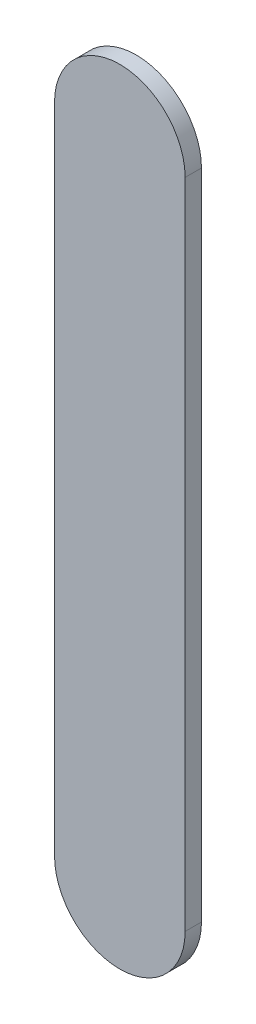
SolidWorks part; units mm, degrees
ref_plane "Front Plane" through (0, 0, 0) normal (0, 0, 1) x (1, 0, 0)
ref_plane "Top Plane" through (0, 0, 0) normal (0, 1, 0) x (1, 0, 0)
ref_plane "Right Plane" through (0, 0, 0) normal (1, 0, 0) x (0, 0, -1)
sketch "Sketch1" plane through (0, 0, 0) normal (0, 0, 1) x (1, 0, 0)
  line L2 (0, 0) -> (0, 40)
  line L4 (8, 0) -> (8, 40)
  arc A0 (8, 40) -> (0, 40) centre (4, 40) ccw
  arc A1 (0, 0) -> (8, 0) centre (4, 0) ccw
  dimension "D1" = 8
  dimension "D2" = 40
extrude "Boss-Extrude1" add sketch "Sketch1" along normal blind 1
